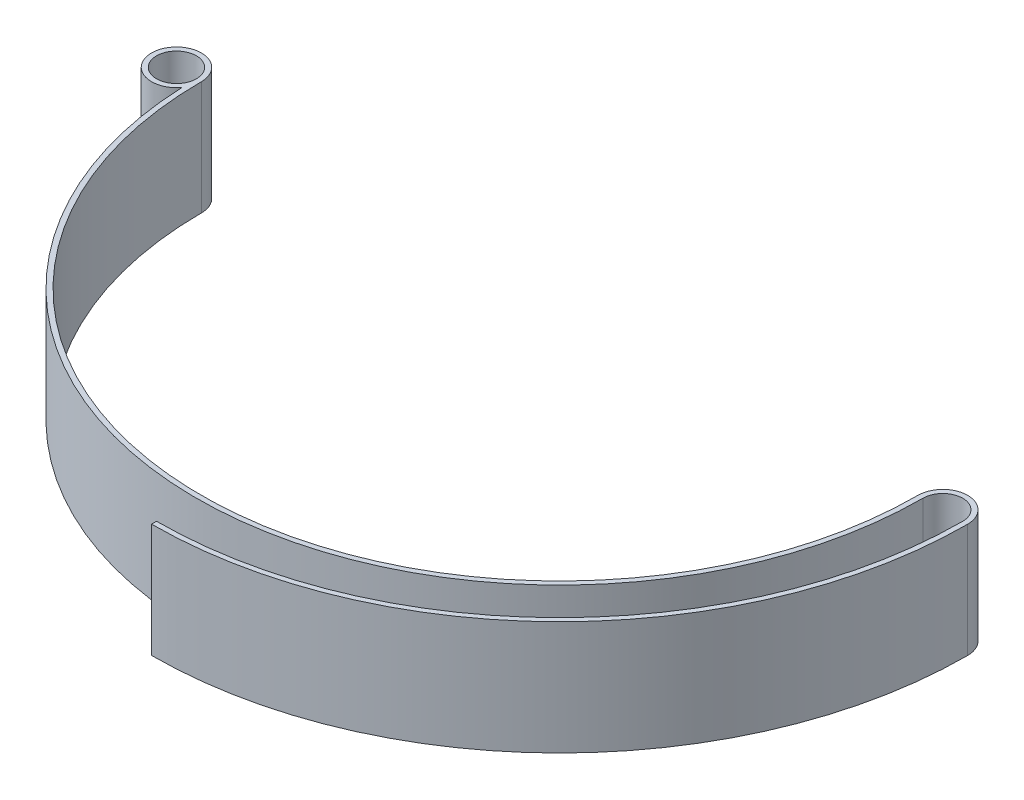
SolidWorks part; units mm, degrees
ref_plane "Front Plane" through (0, 0, 0) normal (0, 0, 1) x (1, 0, 0)
ref_plane "Top Plane" through (0, 0, 0) normal (0, 1, 0) x (1, 0, 0)
ref_plane "Right Plane" through (0, 0, 0) normal (1, 0, 0) x (0, 0, -1)
sketch "Sketch1" plane through (0, 0, 0) normal (0, 1, 0) x (1, 0, 0)
  line L0 (148.69, 0) -> (149.69, 0) construction
  line L1 (76.845, -80.845) -> (76.845, -81.845)
  line L2 (157.69, 0) -> (158.69, 0) construction
  line L3 (76.845, -80.845) -> (76.845, -72.845) construction
  line L4 (149.69, 0) -> (157.69, 0) construction
  circle A0 centre (0, 0) radius 4
  arc A1 (5, 0) -> (148.69, 0) centre (76.845, 0) ccw
  arc A2 (4.0586, -2.9203) -> (149.69, 0) centre (76.845, 0) ccw
  arc A3 (10.4446, -29.9562) -> (149.69, 0) centre (76.845, 0) ccw construction
  arc A5 (5, 0) -> (4.0586, -2.9203) centre (0, 0) ccw
  arc A6 (11.3561, -29.545) -> (148.69, 0) centre (76.845, 0) ccw construction
  arc A7 (148.69, 0) -> (158.69, 0) centre (153.69, 0) cw
  arc A8 (149.69, 0) -> (157.69, 0) centre (153.69, 0) cw
  arc A9 (157.69, 0) -> (76.845, -80.845) centre (76.845, 0) cw
  arc A10 (158.69, 0) -> (76.845, -81.845) centre (76.845, 0) cw
  point P4 (153.69, 5)
  point P31 (5, 0)
  dimension "D1" = 8
  dimension "D5" = 76.845
  dimension "D2" = 153.69
  dimension "D4" = 1
  dimension "D6" = 8
  dimension "D3" = 1
extrude "Boss-Extrude1" add sketch "Sketch1" along normal blind 22.806
equation "\"L\"=0.153690"
equation "\"w\"=0.022806"
equation "\"Loop_D\"=0.008000"
equation "\"t\"=0.001000"
equation "\"fold_back_L\"=0.076845"
equation "\"D1@Sketch1\"=\"Loop_D\"*1000"
equation "\"D5@Sketch1\"=\"fold_back_L\"*1000"
equation "\"D2@Sketch1\"=\"L\"*1000"
equation "\"D4@Sketch1\"=\"t\"*1000"
equation "\"D6@Sketch1\"=\"Loop_D\"*1000"
equation "\"D1@Boss-Extrude1\"=\"w\"*1000"
